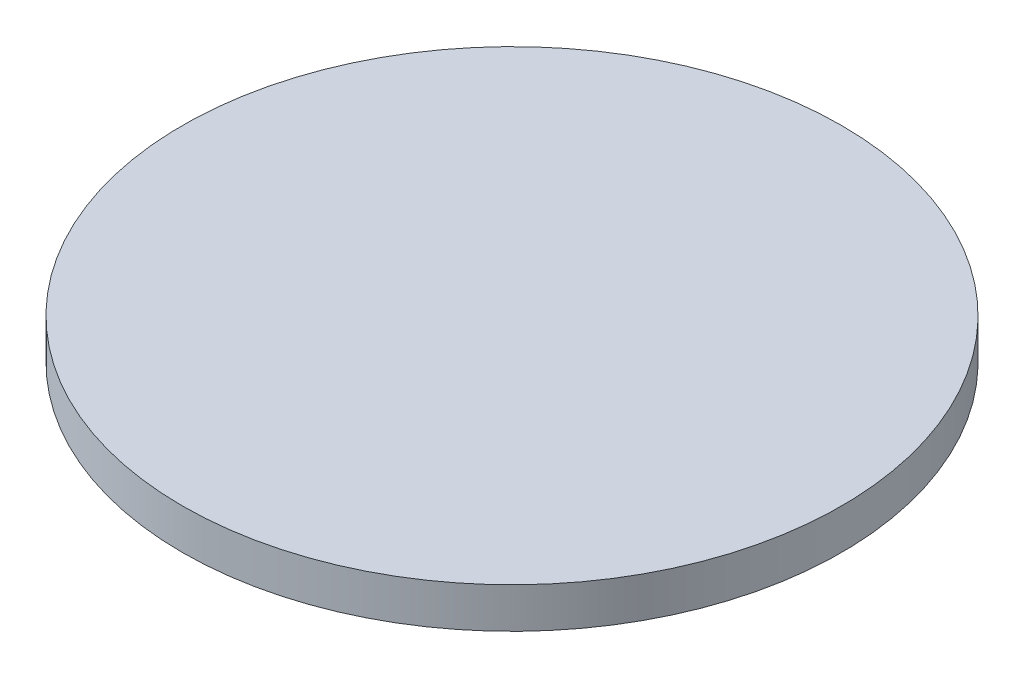
SolidWorks part; units mm, degrees
ref_plane "Спереди" through (0, 0, 0) normal (0, 0, 1) x (1, 0, 0)
ref_plane "Сверху" through (0, 0, 0) normal (0, 1, 0) x (1, 0, 0)
ref_plane "Справа" through (0, 0, 0) normal (1, 0, 0) x (0, 0, -1)
sketch "Эскиз1" plane through (0, 0, 0) normal (0, 1, 0) x (1, 0, 0)
  circle A0 centre (0, 0) radius 24.5
  dimension "D1" = 49
extrude "Бобышка-Вытянуть1" add sketch "Эскиз1" along normal blind 3
